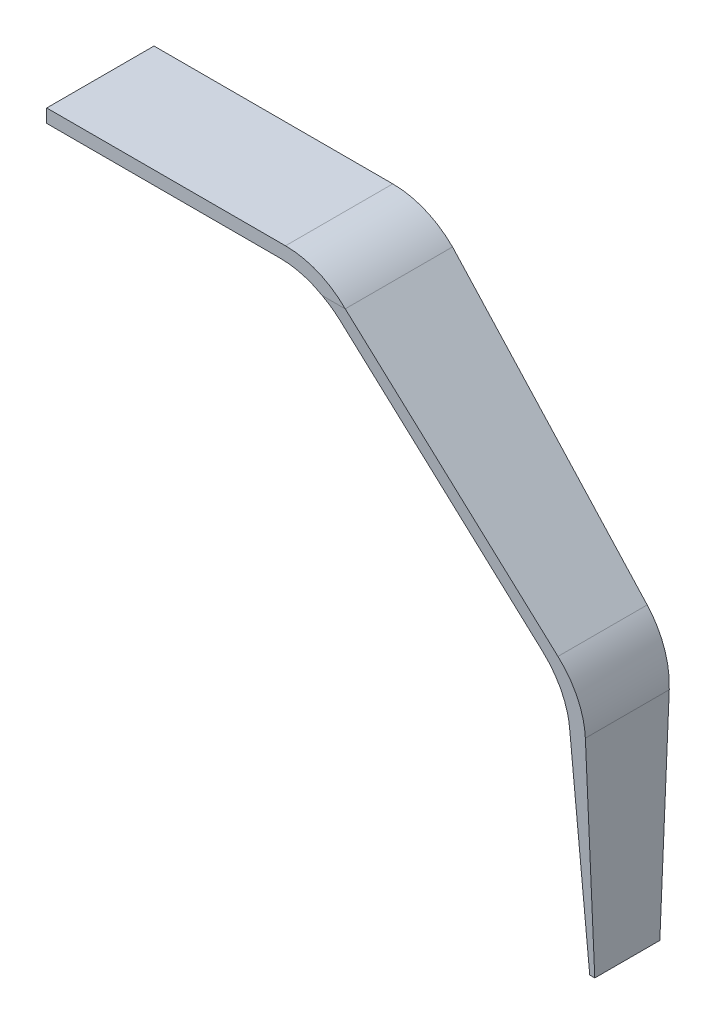
SolidWorks part; units mm, degrees
material "Thornel Mat VMA"
ref_plane "Front Plane" through (0, 0, 0) normal (0, 0, 1) x (1, 0, 0)
ref_plane "Top Plane" through (0, 0, 0) normal (0, 1, 0) x (1, 0, 0)
ref_plane "Right Plane" through (0, 0, 0) normal (1, 0, 0) x (0, 0, -1)
sketch "Sketch1" plane through (0, 0, 0) normal (0, 0, 1) x (1, 0, 0)
  line L0 (5.8579, 51.2921) -> (51.7019, 5.4481)
  line L1 (60.0596, -58.1922) -> (61.2549, -58.1922)
  line L2 (-63.5, 57.15) -> (-63.5, 60.325)
  line L3 (-63.5, 60.325) -> (-6.9691, 60.325)
  line L4 (61.2549, -58.1922) -> (61.2549, -7.8991)
  line L5 (0, 0) -> (30.8201, 30.8201) construction
  line L6 (-63.5, 60.325) -> (61.2549, -58.1922) construction
  line L7 (-63.5, 60.325) -> (1.3151, 60.325)
  line L8 (-63.5, 60.325) -> (-63.5, 57.15)
  line L9 (-63.5, 57.15) -> (-8.2843, 57.15)
  line L10 (57.5348, -7.6952) -> (60.0596, -58.1922)
  line L11 (61.2549, -58.1922) -> (60.0596, -58.1922)
  line L12 (61.2549, -58.1922) -> (61.2549, 0.3852)
  line L16 (54.9049, 6.7352) -> (6.7352, 54.9049)
  line L18 (6.7352, 54.9049) -> (7.173, 54.4671)
  line L19 (54.9049, 6.7352) -> (55.3971, 6.2431)
  arc A0 (51.7019, 5.4481) -> (57.5348, -7.6952) centre (37.5597, -8.694) cw
  arc A1 (55.3971, 6.2431) -> (61.2549, -7.8991) centre (41.2549, -7.8991) cw
  arc A2 (7.173, 54.4671) -> (-6.9691, 60.325) centre (-6.9691, 40.325) ccw
  arc A3 (5.8579, 51.2921) -> (-8.2843, 57.15) centre (-8.2843, 37.15) ccw
  point P0 (0, 0)
  dimension "D1" = 20
  dimension "D3" = 3.175
  dimension "D5" = 3.175
extrude "Boss-Extrude1" add sketch "Sketch1" along normal blind 25.4 contours A3 L0 A0 L10 L1 L4 A1 L19 L16 L18 A2 L3 L2 L9
sketch "Sketch2" plane through (61.2549, 0, 0) normal (1, 0, 0) x (0, 0, -1)
  line L0 (-25.4, 54.4671) -> (-20.4, -58.1922)
  line L1 (-25.4, -58.1922) -> (0, -58.1922) construction
  line L2 (-20.4, -58.1922) -> (-53.9262, -59.6801)
  line L3 (-53.9262, -59.6801) -> (-25.4, 54.4671)
  line L4 (0, 54.4671) -> (-5, -58.1922)
  line L5 (-5, -58.1922) -> (16.3251, -58.1922)
  line L6 (16.3251, -58.1922) -> (0, 54.4671)
  line L7 (-25.4, -58.1922) -> (-25.4, -7.8991) construction
  line L8 (0, -58.1922) -> (0, -7.8991) construction
  dimension "D1" = 5
  dimension "D2" = 5
extrude "Cut-Extrude1" cut sketch "Sketch2" against normal blind 165.4
